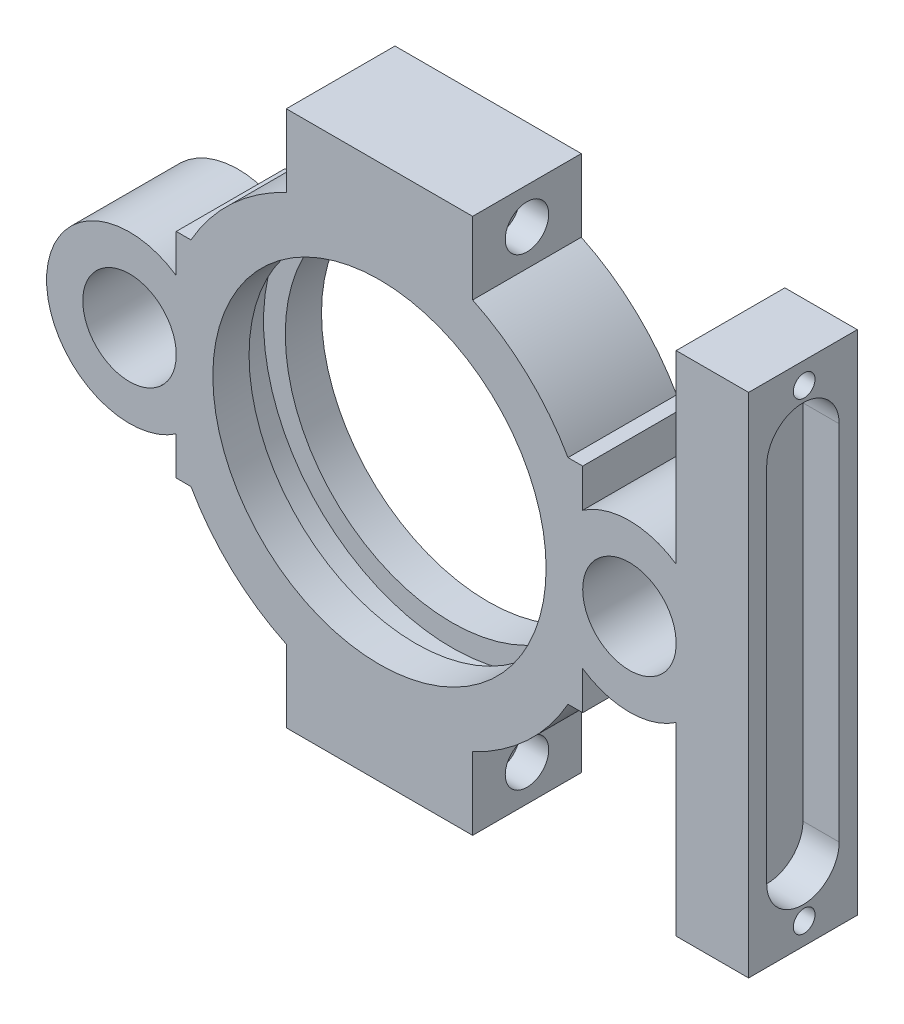
SolidWorks part; units mm, degrees
ref_plane "Front Plane" through (0, 0, 0) normal (0, 0, 1) x (1, 0, 0)
ref_plane "Top Plane" through (0, 0, 0) normal (0, 1, 0) x (1, 0, 0)
ref_plane "Right Plane" through (0, 0, 0) normal (1, 0, 0) x (0, 0, -1)
sketch "Sketch1" plane through (0, 0, 0) normal (0, 0, 1) x (1, 0, 0)
  line L0 (0, 23) -> (0, 37)
  line L1 (0, 37) -> (12.8595, 37)
  line L2 (12.8595, 37) -> (12.8595, 27)
  line L3 (0, 0) -> (90, 0) construction
  line L4 (26.0205, 14.7412) -> (28.0505, 14.7412)
  line L5 (28.0505, 25) -> (28.0505, -25) construction
  line L6 (28.0505, 14.7412) -> (28.0505, 9.4604)
  line L7 (40.9505, 9.4604) -> (40.9505, 35)
  line L8 (40.9505, 35) -> (50.9505, 35)
  line L9 (50.9505, 35) -> (50.9505, -35)
  line L10 (40.9505, -35) -> (50.9505, -35)
  line L11 (40.9505, -9.4604) -> (40.9505, -35)
  line L12 (28.0505, -14.7412) -> (28.0505, -9.4604)
  line L13 (26.0205, -14.7412) -> (28.0505, -14.7412)
  line L14 (12.8595, -37) -> (12.8595, -27)
  line L15 (0, -37) -> (12.8595, -37)
  line L16 (0, -23) -> (0, -37)
  arc A0 (0, 23) -> (0, -23) centre (0, 0) cw
  arc A1 (12.8595, 27) -> (26.0205, 14.7412) centre (0, 0) cw
  circle A2 centre (34.5005, 0) radius 6.45
  arc A3 (28.0505, 9.4604) -> (40.9505, 9.4604) centre (34.5005, 0) cw
  arc A4 (28.0505, -9.4604) -> (40.9505, -9.4604) centre (34.5005, 0) ccw
  arc A5 (12.8595, -27) -> (26.0205, -14.7412) centre (0, 0) ccw
  point P8 (28.0505, 0)
  point P19 (50.9505, 0)
  point P29 (40.9505, 0)
  dimension "D2" = 23
  dimension "D5" = 35
  dimension "D7" = 6.45
  dimension "D8" = 50
  dimension "D9" = 29.906
  dimension "D10" = 11.45
  dimension "D3" = 14
  dimension "D4" = 10
  dimension "D6" = 2.03
  dimension "D11" = 90
  dimension "D12" = 10
  dimension "D13" = 35
extrude "Boss-Extrude1" add sketch "Sketch1" along normal blind 15
ref_plane "Plane1" through (0, 0, 0) normal (-1, 0, 0) x (0, 0, 1)
sketch "Sketch2" plane through (0, 0, 0) normal (-1, 0, 0) x (0, 0, 1)
  line L0 (7.5, 37) -> (7.5, 23) construction
  line L1 (15, 37) -> (0, 37) construction
  line L2 (15, 23) -> (0, 23) construction
  line L3 (10, 26) -> (5, 26)
  line L4 (5, 26) -> (5, 23)
  line L5 (10, 26) -> (10, 23)
  line L6 (5, 23) -> (10, 23)
  line L7 (15, 0) -> (0, 0) construction
  line L8 (15, -23) -> (15, 23) construction
  point P10 (7.5, 26)
  dimension "D1" = 2.5
  dimension "D2" = 3
revolve "Cut-Revolve1" cut sketch "Sketch2" angle 360 about L7
ref_plane "Plane2" through (50.9505, 0, 0) normal (1, 0, 0) x (0, 0, -1)
sketch "Sketch3" plane through (50.9505, 0, 0) normal (1, 0, 0) x (0, 0, -1)
  line L0 (-15, 0) -> (0, 0) construction
  line L1 (-15, -35) -> (-15, 35) construction
  line L2 (-7.5, 35) -> (-7.5, -35) construction
  line L3 (-15, 35) -> (0, 35) construction
  line L5 (-15, -35) -> (0, -35) construction
  line L8 (-12.5, -25) -> (-12.5, 25)
  line L10 (-2.5, -25) -> (-2.5, 25)
  line L11 (-12.5, -25) -> (-2.5, 25) construction
  line L12 (-12.5, 25) -> (-2.5, -25) construction
  arc A0 (-12.5, 25) -> (-2.5, 25) centre (-7.5, 25) cw
  arc A1 (-12.5, -25) -> (-2.5, -25) centre (-7.5, -25) ccw
  point P14 (-7.5, 0)
  dimension "D1" = 50
  dimension "D2" = 10
extrude "Cut-Extrude3" cut sketch "Sketch3" against normal blind 5
ref_plane "Plane3" through (12.8595, 0, 0) normal (1, 0, 0) x (0, 0, -1)
sketch "Sketch4" plane through (12.8595, 0, 0) normal (1, 0, 0) x (0, 0, -1)
  line L0 (-7.5, 37) -> (-7.5, 27) construction
  line L1 (-15, 37) -> (0, 37) construction
  line L2 (-15, 27) -> (0, 27) construction
  line L3 (-15, 32) -> (0, 32) construction
  line L4 (-15, 27) -> (-15, 37) construction
  line L5 (0, 27) -> (0, 37) construction
  line L6 (-15, 0) -> (1.8408, 0) construction
  circle A0 centre (-7.3334, 32) radius 1.5
  circle A1 centre (-7.3334, -32) radius 1.5
  dimension "D1" = 3
extrude "Cut-Extrude4" cut sketch "Sketch4" against normal through all both and the other way through all contours A0 | A1
sketch "Sketch5" plane through (12.8595, 0, 0) normal (1, 0, 0) x (0, 0, -1)
  line L0 (-7.5, 37) -> (-7.5, 27) construction
  line L1 (-15, 37) -> (0, 37) construction
  line L2 (-15, 27) -> (0, 27) construction
  line L3 (-15, 32) -> (0, 32) construction
  line L4 (-15, 27) -> (-15, 37) construction
  line L5 (0, 27) -> (0, 37) construction
  line L6 (-15, 0) -> (6.1086, 0) construction
  circle A0 centre (-7.5, 32) radius 3
  circle A1 centre (-7.5, -32) radius 3
  dimension "D1" = 6
extrude "Cut-Extrude5" cut sketch "Sketch5" against normal blind 4
mirror "Mirror1" about plane through (0, 0, 0) normal (-1, 0, 0) of "Cut-Extrude4", "Cut-Extrude5", "Cut-Revolve1", "Boss-Extrude1"
sketch "Sketch6" plane through (0, 0, 15) normal (0, 0, 1) x (1, 0, 0)
  line L0 (-40.9505, 9.4604) -> (-40.9505, 38.7418)
  line L1 (-40.9505, 38.7418) -> (-62.7725, 38.7418)
  line L2 (-62.7725, 38.7418) -> (-62.7725, -39.4714)
  line L3 (-62.7725, -39.4714) -> (-40.9505, -39.4714)
  line L4 (-40.9505, -39.4714) -> (-40.9505, -9.4604)
  arc A0 (-40.9505, 9.4604) -> (-40.9505, -9.4604) centre (-34.5005, 0) ccw
  dimension "D1" = 22.9
extrude "Cut-Extrude6" cut sketch "Sketch6" against normal blind 80
